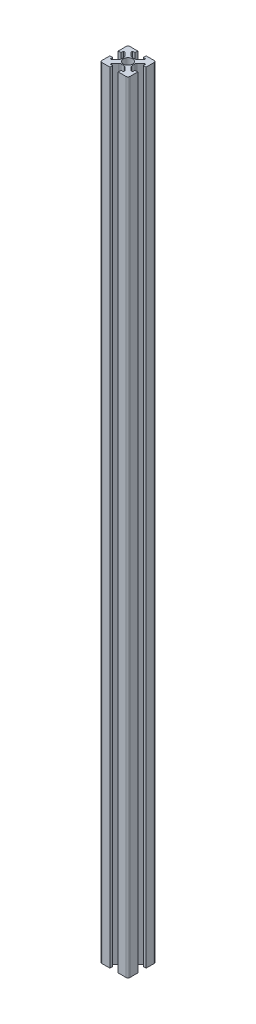
SolidWorks part; units mm, degrees
ref_plane "Front Plane" through (0, 0, 0) normal (0, 0, 1) x (1, 0, 0)
ref_plane "Top Plane" through (0, 0, 0) normal (0, 1, 0) x (1, 0, 0)
ref_plane "Right Plane" through (0, 0, 0) normal (1, 0, 0) x (0, 0, -1)
sketch "Sketch1" plane through (0, 0, 0) normal (0, 1, 0) x (1, 0, 0)
  line L0 (0, 10.4668) -> (0, -7.5) construction
  line L1 (-6.5, 7.5) -> (-2.25, 7.5)
  line L2 (-7.5, 6.5) -> (-7.5, 2.25)
  line L3 (-6.5, -7.5) -> (-2.25, -7.5)
  line L4 (7.5, 6.5) -> (7.5, 2.25)
  line L5 (-7.5, 7.5) -> (7.5, -7.5) construction
  line L6 (-7.5, -7.5) -> (7.5, 7.5) construction
  line L7 (-2.25, 7.5) -> (-2.25, 6)
  line L8 (-2.25, 6) -> (-3.5526, 6)
  line L9 (-3.5526, 6) -> (-3.5526, 5.2802)
  line L10 (-3.5526, 5.2802) -> (-1.6019, 3.3295)
  line L11 (-0.8064, 3) -> (0.8064, 3)
  line L12 (3.5526, 5.2802) -> (1.6019, 3.3295)
  line L13 (3.5526, 6) -> (3.5526, 5.2802)
  line L14 (2.25, 6) -> (3.5526, 6)
  line L15 (2.25, 7.5) -> (2.25, 6)
  line L16 (2.25, 7.5) -> (6.5, 7.5)
  line L17 (7.5, 2.25) -> (6, 2.25)
  line L18 (6, 2.25) -> (6, 3.5526)
  line L19 (6, 3.5526) -> (5.2802, 3.5526)
  line L20 (5.2802, 3.5526) -> (3.3295, 1.6019)
  line L21 (3, 0.8064) -> (3, -0.8064)
  line L22 (5.2802, -3.5526) -> (3.3295, -1.6019)
  line L23 (6, -3.5526) -> (5.2802, -3.5526)
  line L24 (7.5, -2.25) -> (6, -2.25)
  line L25 (6, -2.25) -> (6, -3.5526)
  line L26 (2.25, -7.5) -> (2.25, -6)
  line L27 (2.25, -6) -> (3.5526, -6)
  line L28 (3.5526, -6) -> (3.5526, -5.2802)
  line L29 (3.5526, -5.2802) -> (1.6019, -3.3295)
  line L30 (0.8064, -3) -> (-0.8064, -3)
  line L31 (-3.5526, -5.2802) -> (-1.6019, -3.3295)
  line L32 (-3.5526, -6) -> (-3.5526, -5.2802)
  line L33 (-2.25, -7.5) -> (-2.25, -6)
  line L34 (-2.25, -6) -> (-3.5526, -6)
  line L35 (-7.5, -2.25) -> (-6, -2.25)
  line L36 (-6, -2.25) -> (-6, -3.5526)
  line L37 (-6, -3.5526) -> (-5.2802, -3.5526)
  line L38 (-5.2802, -3.5526) -> (-3.3295, -1.6019)
  line L39 (-3, -0.8064) -> (-3, 0.8064)
  line L40 (-5.2802, 3.5526) -> (-3.3295, 1.6019)
  line L41 (-6, 3.5526) -> (-5.2802, 3.5526)
  line L42 (-7.5, 2.25) -> (-6, 2.25)
  line L43 (-6, 2.25) -> (-6, 3.5526)
  line L44 (7.5, -2.25) -> (7.5, -6.5)
  line L45 (2.25, -7.5) -> (6.5, -7.5)
  line L46 (-7.5, -2.25) -> (-7.5, -6.5)
  arc A0 (6.5, -7.5) -> (7.5, -6.5) centre (6.5, -6.5) ccw
  arc A1 (-7.5, -6.5) -> (-6.5, -7.5) centre (-6.5, -6.5) ccw
  arc A2 (6.5, 7.5) -> (7.5, 6.5) centre (6.5, 6.5) cw
  arc A3 (-6.5, 7.5) -> (-7.5, 6.5) centre (-6.5, 6.5) ccw
  arc A4 (-3.3295, -1.6019) -> (-3, -0.8064) centre (-4.125, -0.8064) ccw
  arc A5 (-3, 0.8064) -> (-3.3295, 1.6019) centre (-4.125, 0.8064) ccw
  arc A6 (-1.6019, 3.3295) -> (-0.8064, 3) centre (-0.8064, 4.125) ccw
  arc A7 (1.6019, 3.3295) -> (0.8064, 3) centre (0.8064, 4.125) cw
  arc A8 (3.3295, 1.6019) -> (3, 0.8064) centre (4.125, 0.8064) ccw
  arc A9 (3, -0.8064) -> (3.3295, -1.6019) centre (4.125, -0.8064) ccw
  arc A10 (1.6019, -3.3295) -> (0.8064, -3) centre (0.8064, -4.125) ccw
  arc A11 (-0.8064, -3) -> (-1.6019, -3.3295) centre (-0.8064, -4.125) ccw
  point P0 (0, 0)
  point P15 (0, 3)
  point P19 (0, 0)
  point P32 (0, 0)
  point P43 (0, 0)
  point P54 (0, 0)
  point P71 (-1.2724, 3)
  point P74 (1.2724, 3)
  dimension "D9" = 1
  dimension "D10" = 1.125
  dimension "D1" = 2.5448
  dimension "D2" = 4.5
  dimension "D3" = 1.5
  dimension "D4" = 135
  dimension "D5" = 3
  dimension "D6" = 2.5448
  dimension "D7" = 5.25
  dimension "D8" = 4
extrude "Boss-Extrude1" add sketch "Sketch1" along normal blind 420
sketch "Sketch3" plane through (0, 420, 0) normal (0, 1, 0) x (1, 0, 0)
  circle A0 centre (0, 0) radius 2.5
extrude "Cut-Extrude1" cut sketch "Sketch3" against normal through all both and the other way through all
